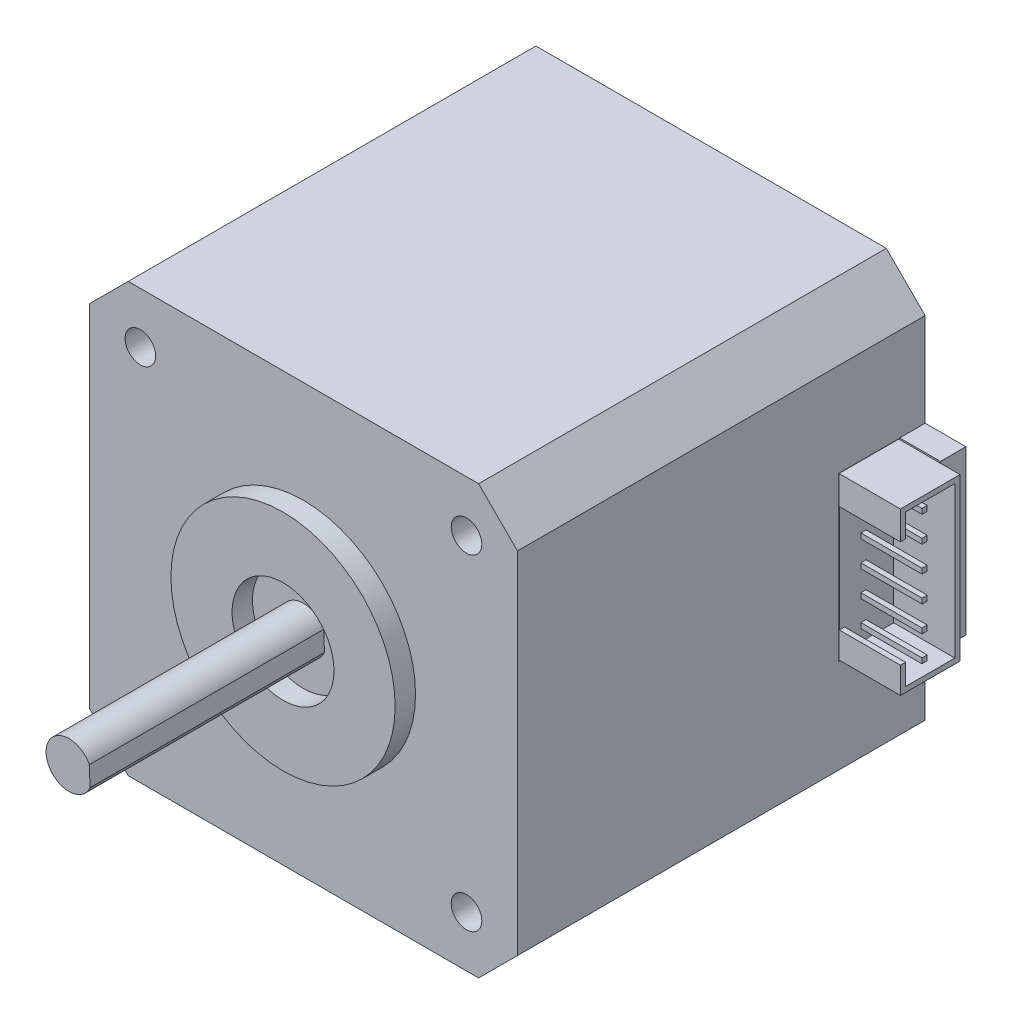
SolidWorks part; units mm, degrees
ref_plane "Front" through (0, 0, 0) normal (0, 0, 1) x (1, 0, 0)
ref_plane "Top" through (0, 0, 0) normal (0, 1, 0) x (1, 0, 0)
ref_plane "Right" through (0, 0, 0) normal (1, 0, 0) x (0, 0, -1)
sketch "Sketch1" plane through (0, 0, 0) normal (0, 0, 1) x (1, 0, 0)
  line L1 (0, 0) -> (42, 0)
  line L2 (0, 0) -> (0, -42)
  line L3 (0, -42) -> (42, -42)
  line L4 (42, 0) -> (42, -42)
  dimension "D1" = 42
  dimension "D2" = 42
extrude "Boss-Extrude1" add sketch "Sketch1" along normal blind 40
sketch "Sketch2" plane through (0, 0, 40) normal (0, 0, 1) x (1, 0, 0)
  line L0 (21, 0) -> (21, -42) construction
  line L1 (42, 0) -> (0, 0) construction
  line L2 (0, -42) -> (42, -42) construction
  circle A0 centre (21, -21) radius 11
  circle A1 centre (21, -21) radius 5
  dimension "D1" = 22
  dimension "D2" = 10
extrude "Boss-Extrude2" add sketch "Sketch2" along normal blind 2
sketch "Sketch3" plane through (0, 0, 40) normal (0, 0, 1) x (1, 0, 0)
  line L0 (23.0631, -21.8979) -> (22.9987, -19.9667)
  arc A0 (22.9987, -19.9667) -> (23.0631, -21.8979) centre (21, -21) ccw
  dimension "D1" = 4.5
  dimension "D2" = 2.032
  dimension "D3" = 1.9313
extrude "Boss-Extrude3" add sketch "Sketch3" along normal blind 23
sketch "Sketch4" plane through (0, 0, 40) normal (0, 0, 1) x (1, 0, 0)
  line L0 (5, 0) -> (5, -42) construction
  line L1 (42, 0) -> (0, 0) construction
  line L2 (0, -42) -> (42, -42) construction
  line L3 (21, 0) -> (21, -42) construction
  line L4 (0, 0) -> (0, -42) construction
  circle A0 centre (5, -5) radius 1.5
  circle A1 centre (5, -37) radius 1.5
  circle A2 centre (37, -5) radius 1.5
  circle A3 centre (37, -37) radius 1.5
  dimension "D2" = 5
  dimension "D4" = 3
  dimension "D5" = 3
  dimension "D1" = 5
  dimension "D3" = 5
extrude "Cut-Extrude1" cut sketch "Sketch4" against normal blind 2.68
sketch "Sketch5" plane through (0, 0, 0) normal (0, 0, -1) x (-1, 0, 0)
  line L0 (-21, 0) -> (-21, -42) construction
  line L1 (-42, 0) -> (0, 0) construction
  line L2 (0, -42) -> (-42, -42) construction
  line L3 (-37, 0) -> (-37, -42) construction
  line L4 (-42, -42) -> (-42, 0) construction
  circle A0 centre (-37, -5) radius 3
  circle A1 centre (-37, -37) radius 3
  circle A2 centre (-5, -37) radius 3
  circle A3 centre (-5, -5) radius 3
  dimension "D2" = 6
  dimension "D3" = 6
  dimension "D4" = 5
  dimension "D5" = 5
  dimension "D1" = 5
extrude "Cut-Extrude2" cut sketch "Sketch5" against normal blind 2.68
sketch "Sketch6" plane through (0, 0, 0) normal (0, 0, -1) x (-1, 0, 0)
  line L0 (-21, 0) -> (-21, -42) construction
  line L1 (-42, 0) -> (0, 0) construction
  line L2 (0, -42) -> (-42, -42) construction
  circle A0 centre (-21, -21) radius 5
  dimension "D1" = 10
extrude "Cut-Extrude3" cut sketch "Sketch6" against normal blind 2.68
sketch "Sketch7" plane through (0, 0, 2.68) normal (0, 0, -1) x (-1, 0, 0)
  circle A0 centre (-21, -21) radius 3.5
  circle A1 centre (-21, -21) radius 2.5
  circle A2 centre (-21, -21) radius 3.4238
  circle A3 centre (-21, -21) radius 2.4238
  dimension "D1" = 7
  dimension "D2" = 5
  dimension "D3" = 0.0762
  dimension "D4" = 0.0762
extrude "Cut-Extrude4" cut sketch "Sketch7" against normal blind 0.0254 contours A0 A2 | A1 A3
chamfer "Chamfer1" distance 3.81 angle 45 4 edges at (0, -42, 20) (42, -42, 20) (0, 0, 20) (42, 0, 20)
sketch "Sketch8" plane through (42, 0, 0) normal (1, 0, 0) x (0, 0, -1)
  line L1 (0, -28.954) -> (-2.5, -28.954)
  line L2 (0, -28.954) -> (0, -12.954)
  line L3 (0, -12.954) -> (-2.5, -12.954)
  line L4 (-2.5, -28.954) -> (-2.5, -12.954)
  line L7 (0, -3.81) -> (-40, -3.81) construction
  line L9 (0, -38.19) -> (0, -3.81) construction
  dimension "D1" = 9.144
  dimension "D2" = 16
  dimension "D3" = 0
  dimension "D4" = 2.5
extrude "Boss-Extrude4" add sketch "Sketch8" along normal blind 4
sketch "Sketch9" plane through (42, 0, 0) normal (1, 0, 0) x (0, 0, -1)
  line L0 (-2.5762, -28.8778) -> (-8.4238, -28.8778)
  line L1 (-2.5, -28.954) -> (-8.5, -28.954)
  line L2 (-2.5, -28.954) -> (-2.5, -12.954)
  line L3 (-2.5, -12.954) -> (-8.5, -12.954)
  line L4 (-8.5, -28.954) -> (-8.5, -12.954)
  line L5 (-8.4238, -28.8778) -> (-8.4238, -13.0302)
  line L6 (-2.5762, -13.0302) -> (-8.4238, -13.0302)
  line L7 (-2.5762, -28.8778) -> (-2.5762, -13.0302)
  dimension "D1" = 6
  dimension "D2" = 0.0762
extrude "Cut-Extrude5" cut sketch "Sketch9" against normal blind 0.0254
sketch "Sketch10" plane through (42, 0, 0) normal (1, 0, 0) x (0, 0, -1)
  line L0 (-7.9158, -28.3698) -> (-7.9158, -26.3114)
  line L1 (-8.4238, -28.8778) -> (-2.5762, -28.8778)
  line L2 (-8.4238, -28.8778) -> (-8.4238, -26.3114)
  line L3 (-8.4238, -13.0302) -> (-2.5762, -13.0302)
  line L4 (-2.5762, -28.8778) -> (-2.5762, -13.0302)
  line L5 (-7.9158, -13.5382) -> (-3.0842, -13.5382)
  line L6 (-3.0842, -28.3698) -> (-3.0842, -13.5382)
  line L7 (-7.9158, -28.3698) -> (-3.0842, -28.3698)
  line L8 (-7.9158, -15.8274) -> (-7.9158, -13.5382)
  line L9 (-8.4238, -26.3114) -> (-7.9158, -26.3114)
  line L10 (-6.091, -28.3698) -> (-6.091, -13.5382) construction
  line L11 (-8.4238, -15.8274) -> (-7.9158, -15.8274)
  line L12 (-5.8042, -24.7049) -> (-5.8042, -24.1969)
  line L13 (-7.9158, -28.3698) -> (-7.9158, -13.5382) construction
  line L14 (-8.4238, -15.8274) -> (-8.4238, -13.0302)
  line L15 (-8.4238, -28.8778) -> (-8.4238, -13.0302) construction
  line L17 (-6.3122, -27.2449) -> (-5.8042, -27.2449)
  line L18 (-6.3122, -27.2449) -> (-6.3122, -26.7369)
  line L19 (-6.3122, -26.7369) -> (-5.8042, -26.7369)
  line L20 (-5.8042, -27.2449) -> (-5.8042, -26.7369)
  line L21 (-6.3122, -24.7049) -> (-5.8042, -24.7049)
  line L22 (-6.3122, -24.7049) -> (-6.3122, -24.1969)
  line L23 (-6.3122, -24.1969) -> (-5.8042, -24.1969)
  line L24 (-5.8042, -22.1649) -> (-5.8042, -21.6569)
  line L25 (-6.3122, -22.1649) -> (-5.8042, -22.1649)
  line L26 (-6.3122, -22.1649) -> (-6.3122, -21.6569)
  line L27 (-6.3122, -21.6569) -> (-5.8042, -21.6569)
  line L28 (-5.8042, -19.6249) -> (-5.8042, -19.1169)
  line L29 (-6.3122, -19.6249) -> (-5.8042, -19.6249)
  line L30 (-6.3122, -19.6249) -> (-6.3122, -19.1169)
  line L31 (-6.3122, -19.1169) -> (-5.8042, -19.1169)
  line L32 (-5.8042, -17.0849) -> (-5.8042, -16.5769)
  line L33 (-6.3122, -17.0849) -> (-5.8042, -17.0849)
  line L34 (-6.3122, -17.0849) -> (-6.3122, -16.5769)
  line L35 (-6.3122, -16.5769) -> (-5.8042, -16.5769)
  line L36 (-5.8042, -14.5449) -> (-5.8042, -14.0369)
  line L37 (-6.3122, -14.5449) -> (-5.8042, -14.5449)
  line L38 (-6.3122, -14.5449) -> (-6.3122, -14.0369)
  line L39 (-6.3122, -14.0369) -> (-5.8042, -14.0369)
  dimension "D2" = 0.508
  dimension "D3" = 0.508
  dimension "D1" = 0.508
  dimension "D4" = 6
extrude "Boss-Extrude5" add sketch "Sketch10" along normal blind 6
